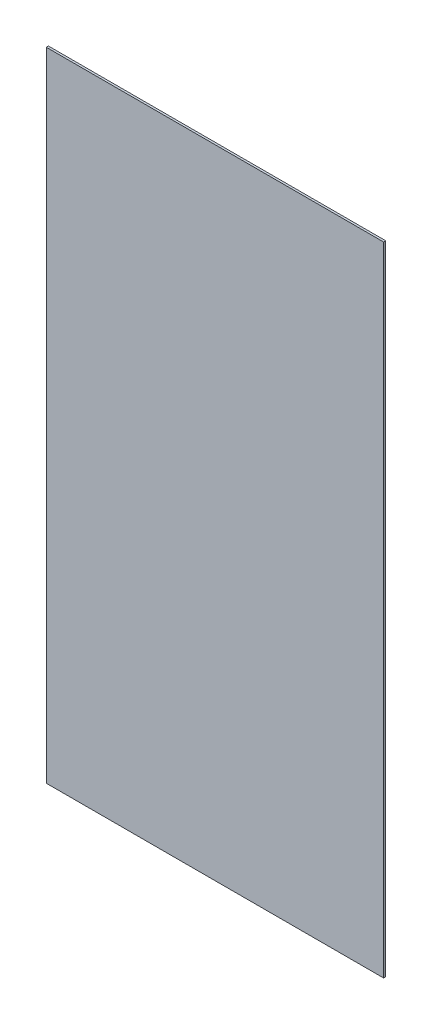
SolidWorks part; units mm, degrees
material "Acrylic (Medium-high impact)"
ref_plane "Front Plane" through (0, 0, 0) normal (0, 0, 1) x (1, 0, 0)
ref_plane "Top Plane" through (0, 0, 0) normal (0, 1, 0) x (1, 0, 0)
ref_plane "Right Plane" through (0, 0, 0) normal (1, 0, 0) x (0, 0, -1)
sketch "Sketch1" plane through (0, 0, 0) normal (0, 0, 1) x (1, 0, 0)
  line L1 (-317.5, -600) -> (317.5, -600)
  line L2 (-317.5, -600) -> (-317.5, 600)
  line L3 (-317.5, 600) -> (317.5, 600)
  line L4 (317.5, -600) -> (317.5, 600)
  line L5 (-317.5, -600) -> (317.5, 600) construction
  line L6 (-317.5, 600) -> (317.5, -600) construction
  point P0 (0, 0)
  dimension "D1" = 635
  dimension "D2" = 1200
extrude "Boss-Extrude1" add sketch "Sketch1" along normal blind 4
